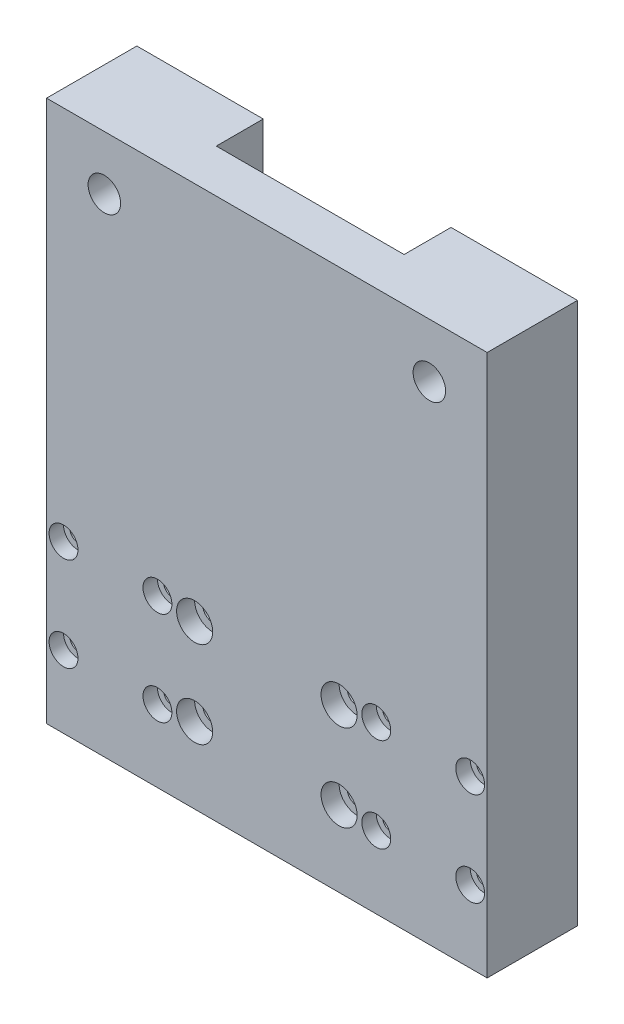
SolidWorks part; units mm, degrees
ref_plane "Front Plane" through (0, 0, 0) normal (0, 0, 1) x (1, 0, 0)
ref_plane "Top Plane" through (0, 0, 0) normal (0, 1, 0) x (1, 0, 0)
ref_plane "Right Plane" through (0, 0, 0) normal (1, 0, 0) x (0, 0, -1)
sketch "Sketch1" plane through (0, 0, 0) normal (0, 0, 1) x (1, 0, 0)
  line L1 (0, 0) -> (122, 0)
  line L2 (0, 0) -> (0, 150)
  line L3 (0, 150) -> (122, 150)
  line L4 (122, 0) -> (122, 150)
  dimension "D1" = 122
  dimension "D2" = 150
extrude "Boss-Extrude1" add sketch "Sketch1" along normal blind 25
sketch "Sketch2" plane through (0, 0, 25) normal (0, 0, 1) x (1, 0, 0)
  line L0 (61, 150) -> (61, 0) construction
  line L1 (122, 150) -> (0, 150) construction
  line L2 (0, 0) -> (122, 0) construction
  line L3 (0, 33) -> (122, 33) construction
  line L4 (0, 150) -> (0, 0) construction
  line L5 (122, 0) -> (122, 150) construction
  point P6 (30.7, 20)
  point P7 (30.7, 46)
  point P8 (4.7, 20)
  point P9 (4.7, 46)
  point P10 (117.3, 46)
  point P11 (117.3, 20)
  point P12 (91.3, 46)
  point P13 (91.3, 20)
  point P20 (41, 45)
  point P21 (81, 45)
  point P22 (81, 21)
  point P23 (41, 21)
  dimension "D1" = 30.3
  dimension "D2" = 26
  dimension "D3" = 26
  dimension "D4" = 20
  dimension "D5" = 13
  dimension "D6" = 12
  dimension "D7" = 20
hole_wizard "CBORE for M4 SHCS1" positions "3DSketch1" profile "Sketch3" counterbore size "M4" standard "ANSI Metric" end condition through all
sketch3d "3DSketch1"
  point P0 (4.7, 46, 25)
  point P3 (30.7, 46, 25)
  point P6 (4.7, 20, 25)
  point P9 (30.7, 20, 25)
  point P12 (91.3, 46, 25)
  point P15 (117.3, 46, 25)
  point P18 (117.3, 20, 25)
  point P21 (91.3, 20, 25)
sketch "Sketch3" plane through (4.7, 46, 25) normal (1, 0, 0) x (0, -1, 0)
  line L0 (0, 0) -> (0, 25)
  line L1 (0, 25) -> (2.25, 25)
  line L3 (2.25, 25) -> (2.25, 4)
  line L4 (2.25, 4) -> (4, 4)
  line L5 (4, 4) -> (4, 0)
  line L7 (4, 0) -> (0, 0)
  line L11 (0, -6.35) -> (0, 107.95) construction
  dimension "Thru Hole Dia." = 4.5
  dimension "Thru Hole Depth" = 25
  dimension "C'Bore Dia." = 8
  dimension "C'Bore Depth" = 4
sketch "Sketch4" plane through (0, 0, 0) normal (0, 1, 0) x (1, 0, 0)
  line L0 (61, 0) -> (61, -20.062) construction
  line L1 (122, 0) -> (0, 0) construction
  line L2 (35, 0) -> (35, -13)
  line L3 (35, -13) -> (87, -13)
  line L4 (87, 0) -> (87, -13)
  line L5 (35, 0) -> (87, 0)
  point P8 (61, -13)
  dimension "D1" = 26
  dimension "D2" = 13
extrude "Cut-Extrude1" cut sketch "Sketch4" along normal through all
hole_wizard "CBORE for M5 SHCS1" positions "3DSketch3" profile "Sketch7" counterbore size "M5" standard "ANSI Metric" end condition through all
sketch3d "3DSketch3"
  point P0 (41, 45, 25)
  point P3 (81, 45, 25)
  point P6 (81, 21, 25)
  point P9 (41, 21, 25)
sketch "Sketch7" plane through (41, 45, 25) normal (1, 0, 0) x (0, -1, 0)
  line L0 (0, 0) -> (0, 25)
  line L1 (0, 25) -> (2.75, 25)
  line L3 (2.75, 25) -> (2.75, 5)
  line L4 (2.75, 5) -> (5, 5)
  line L5 (5, 5) -> (5, 0)
  line L7 (5, 0) -> (0, 0)
  line L11 (0, -6.35) -> (0, 107.95) construction
  dimension "Thru Hole Dia." = 5.5
  dimension "Thru Hole Depth" = 25
  dimension "C'Bore Dia." = 10
  dimension "C'Bore Depth" = 5
sketch "Sketch8" plane through (0, 0, 0) normal (0, 0, -1) x (-1, 0, 0)
  line L0 (-87, 135) -> (-35, 135) construction
  line L1 (-87, 0) -> (-87, 150) construction
  line L2 (-35, 0) -> (-35, 150) construction
  line L3 (-35, 150) -> (-87, 150) construction
  line L4 (-61, 150) -> (-61, 0) construction
  line L5 (-61, 150) -> (-61, 122.8733) construction
  point P8 (-106, 135)
  point P14 (-16, 135)
  dimension "D1" = 15
  dimension "D2" = 45
hole_wizard "CBORE for M8 SHCS1" positions "3DSketch5" profile "Sketch10" counterbore size "M8" standard "ANSI Metric" end condition through all
sketch3d "3DSketch5"
  point P0 (106, 135, 0)
  point P3 (16, 135, 0)
sketch "Sketch10" plane through (106, 135, 0) normal (1, 0, 0) x (0, 1, 0)
  line L0 (0, 0) -> (0, 25)
  line L1 (0, 25) -> (4.5, 25)
  line L3 (4.5, 25) -> (4.5, 8)
  line L4 (4.5, 8) -> (7.5, 8)
  line L5 (7.5, 8) -> (7.5, 0)
  line L7 (7.5, 0) -> (0, 0)
  line L11 (0, -6.35) -> (0, 107.95) construction
  dimension "Thru Hole Dia." = 9
  dimension "Thru Hole Depth" = 25
  dimension "C'Bore Dia." = 15
  dimension "C'Bore Depth" = 8
